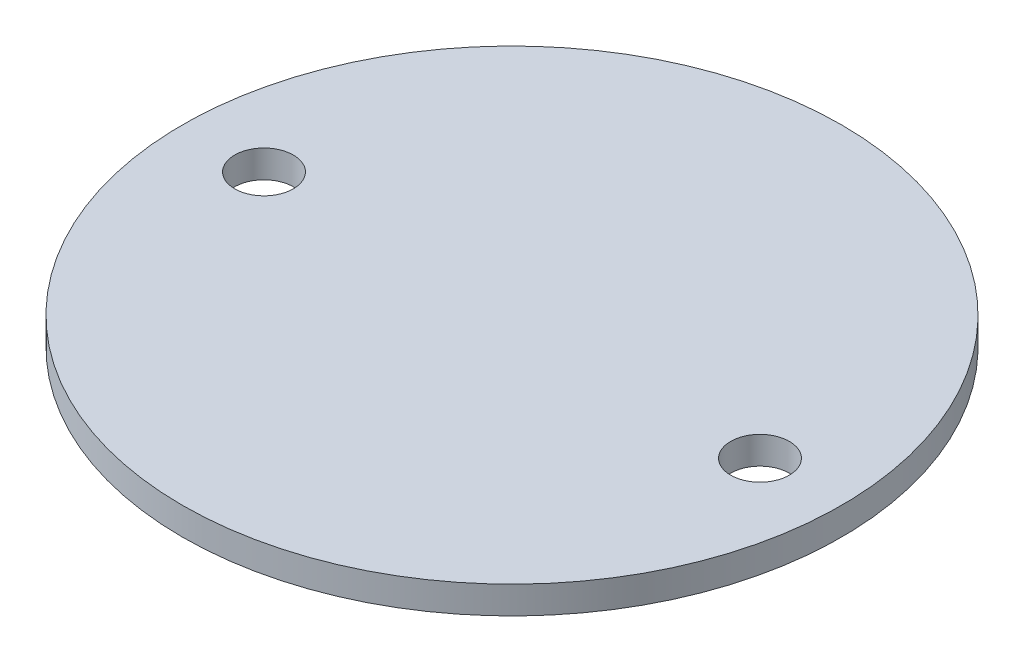
SolidWorks part; units mm, degrees
ref_plane "Front Plane" through (0, 0, 0) normal (0, 0, 1) x (1, 0, 0)
ref_plane "Top Plane" through (0, 0, 0) normal (0, 1, 0) x (1, 0, 0)
ref_plane "Right Plane" through (0, 0, 0) normal (1, 0, 0) x (0, 0, -1)
sketch "Sketch1" plane through (0, 0, 0) normal (0, 1, 0) x (1, 0, 0)
  circle A0 centre (0, 0) radius 37.973
  dimension "D1" = 75.946
extrude "Boss-Extrude1" add sketch "Sketch1" along normal mid plane 3.175
hole_wizard "H (0.266) Diameter Hole1" positions "Sketch2" profile "Sketch3" hole size "H" standard "ANSI Inch" end condition through all
sketch "Sketch2" plane through (0, 1.5875, 0) normal (0, 1, 0) x (1, 0, 0)
  line L0 (-28.575, 0) -> (28.575, 0) construction
  point P0 (-28.575, 0)
  point P2 (28.575, 0)
  dimension "D1" = 57.15
sketch "Sketch3" plane through (-28.575, 1.5875, 0) normal (1, 0, 0) x (0, 0, 1)
  line L0 (0, 0) -> (0, 3.175)
  line L1 (0, 3.175) -> (3.3782, 3.175)
  line L2 (3.3782, 3.175) -> (3.3782, 0)
  line L5 (3.3782, 0) -> (0, 0)
  line L11 (0, -6.35) -> (0, 107.95) construction
  dimension "Thru Hole Dia." = 6.7564
  dimension "Thru Hole Depth" = 3.175
equation "\"airframeInnerDiameter\"=3"
equation "\"airframeBulkheadThickness\"=0.125"
equation "\"D1@Boss-Extrude1\"=\"airframeBulkheadThickness\""
equation "\"recoveryBayInnerDiameter\"=2.88"
equation "\"D1@Sketch1\"    = \"airframeInnerDiameter\"-0.01"
equation "\"threaded rod distance\"= 2.25"
equation "\"D1@Sketch2\"=\"threaded rod distance\""
